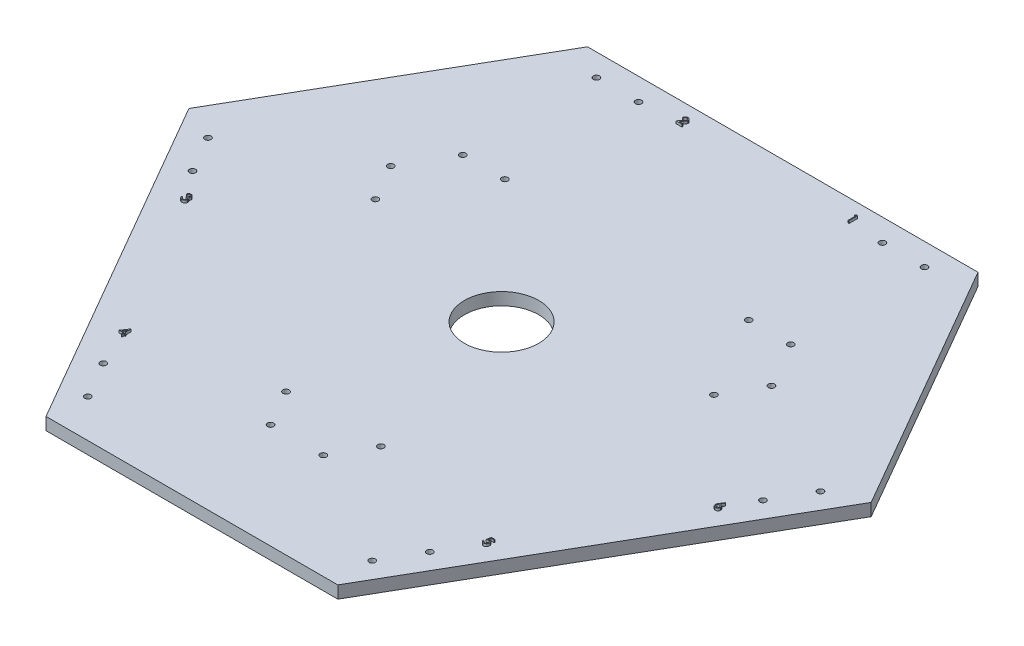
SolidWorks part; units mm, degrees
ref_plane "Front Plane" through (0, 0, 0) normal (0, 0, 1) x (1, 0, 0)
ref_plane "Top Plane" through (0, 0, 0) normal (0, 1, 0) x (1, 0, 0)
ref_plane "Right Plane" through (0, 0, 0) normal (1, 0, 0) x (0, 0, -1)
sketch "Sketch1" plane through (0, 0, 0) normal (0, 1, 0) x (1, 0, 0)
  line L0 (0, 0) -> (-57.7186, 110.8764) construction
  line L9 (0, 0) -> (0, 125) construction
  line L15 (0, 0) -> (57.7186, 110.8764) construction
  line L16 (-57.7186, 110.8764) -> (-12.7186, 110.8764) construction
  line L17 (-57.7186, 108.5064) -> (-57.7186, 110.8764) construction
  line L18 (-66.2186, 104.5064) -> (-49.2186, 104.5064) construction
  line L19 (-66.2186, 104.5064) -> (-66.2186, 50.5064) construction
  line L20 (-66.2186, 50.5064) -> (-49.2186, 50.5064) construction
  line L21 (-49.2186, 104.5064) -> (-49.2186, 50.5064) construction
  line L26 (-66.2186, 104.5064) -> (-49.2186, 50.5064) construction
  line L27 (-66.2186, 50.5064) -> (-49.2186, 104.5064) construction
  line L30 (-43.2186, 46.5064) -> (-72.2186, 46.5064) construction
  line L31 (-43.2186, 46.5064) -> (-43.2186, 108.5064) construction
  line L32 (-43.2186, 108.5064) -> (-72.2186, 108.5064) construction
  line L34 (-72.2186, 46.5064) -> (-72.2186, 108.5064) construction
  line L35 (-43.2186, 46.5064) -> (-72.2186, 108.5064) construction
  line L36 (-43.2186, 108.5064) -> (-72.2186, 46.5064) construction
  line L37 (43.2186, 108.5064) -> (72.2186, 46.5064) construction
  line L38 (43.2186, 46.5064) -> (72.2186, 108.5064) construction
  line L39 (72.2186, 46.5064) -> (72.2186, 108.5064) construction
  line L40 (43.2186, 108.5064) -> (72.2186, 108.5064) construction
  line L41 (43.2186, 46.5064) -> (43.2186, 108.5064) construction
  line L42 (43.2186, 46.5064) -> (72.2186, 46.5064) construction
  line L43 (66.2186, 50.5064) -> (49.2186, 104.5064) construction
  line L44 (66.2186, 104.5064) -> (49.2186, 50.5064) construction
  line L45 (49.2186, 104.5064) -> (49.2186, 50.5064) construction
  line L46 (66.2186, 50.5064) -> (49.2186, 50.5064) construction
  line L47 (66.2186, 104.5064) -> (66.2186, 50.5064) construction
  line L48 (66.2186, 104.5064) -> (49.2186, 104.5064) construction
  line L49 (57.7186, 108.5064) -> (57.7186, 110.8764) construction
  line L50 (57.7186, 110.8764) -> (12.7186, 110.8764) construction
  line L51 (0, 0) -> (124.881, -5.4524) construction
  line L52 (0, 0) -> (108.2532, -62.5) construction
  line L53 (0, 0) -> (67.1625, -105.4239) construction
  line L54 (124.881, -5.4524) -> (102.381, -44.4236) construction
  line L55 (122.8285, -4.2674) -> (124.881, -5.4524) construction
  line L56 (123.6144, 5.0938) -> (115.1144, -9.6286) construction
  line L57 (123.6144, 5.0938) -> (76.8491, 32.0938) construction
  line L58 (76.8491, 32.0938) -> (68.3491, 17.3714) construction
  line L59 (115.1144, -9.6286) -> (68.3491, 17.3714) construction
  line L60 (123.6144, 5.0938) -> (68.3491, 17.3714) construction
  line L61 (76.8491, 32.0938) -> (115.1144, -9.6286) construction
  line L62 (61.885, 14.1752) -> (76.385, 39.2899) construction
  line L63 (61.885, 14.1752) -> (115.5785, -16.8248) construction
  line L64 (115.5785, -16.8248) -> (130.0785, 8.2899) construction
  line L65 (76.385, 39.2899) -> (130.0785, 8.2899) construction
  line L66 (61.885, 14.1752) -> (130.0785, 8.2899) construction
  line L67 (115.5785, -16.8248) -> (76.385, 39.2899) construction
  line L68 (72.36, -91.6816) -> (4.1664, -85.7963) construction
  line L69 (18.6664, -60.6816) -> (57.86, -116.7963) construction
  line L70 (4.1664, -85.7963) -> (57.86, -116.7963) construction
  line L71 (72.36, -91.6816) -> (57.86, -116.7963) construction
  line L72 (18.6664, -60.6816) -> (72.36, -91.6816) construction
  line L73 (18.6664, -60.6816) -> (4.1664, -85.7963) construction
  line L74 (10.6305, -82.6001) -> (65.8959, -94.8777) construction
  line L75 (57.3959, -109.6001) -> (19.1305, -67.8777) construction
  line L76 (65.8959, -94.8777) -> (19.1305, -67.8777) construction
  line L77 (10.6305, -82.6001) -> (19.1305, -67.8777) construction
  line L78 (57.3959, -109.6001) -> (10.6305, -82.6001) construction
  line L79 (57.3959, -109.6001) -> (65.8959, -94.8777) construction
  line L80 (65.11, -104.2389) -> (67.1625, -105.4239) construction
  line L81 (67.1625, -105.4239) -> (89.6625, -66.4528) construction
  line L82 (0, 0) -> (-67.1625, -105.4239) construction
  line L83 (0, 0) -> (-108.2532, -62.5) construction
  line L84 (0, 0) -> (-124.881, -5.4524) construction
  line L85 (-67.1625, -105.4239) -> (-89.6625, -66.4528) construction
  line L86 (-65.11, -104.2389) -> (-67.1625, -105.4239) construction
  line L87 (-57.3959, -109.6001) -> (-65.8959, -94.8777) construction
  line L88 (-57.3959, -109.6001) -> (-10.6305, -82.6001) construction
  line L89 (-10.6305, -82.6001) -> (-19.1305, -67.8777) construction
  line L90 (-65.8959, -94.8777) -> (-19.1305, -67.8777) construction
  line L91 (-57.3959, -109.6001) -> (-19.1305, -67.8777) construction
  line L92 (-10.6305, -82.6001) -> (-65.8959, -94.8777) construction
  line L93 (-18.6664, -60.6816) -> (-4.1664, -85.7963) construction
  line L94 (-18.6664, -60.6816) -> (-72.36, -91.6816) construction
  line L95 (-72.36, -91.6816) -> (-57.86, -116.7963) construction
  line L96 (-4.1664, -85.7963) -> (-57.86, -116.7963) construction
  line L97 (-18.6664, -60.6816) -> (-57.86, -116.7963) construction
  line L98 (-72.36, -91.6816) -> (-4.1664, -85.7963) construction
  line L99 (-115.5785, -16.8248) -> (-76.385, 39.2899) construction
  line L100 (-61.885, 14.1752) -> (-130.0785, 8.2899) construction
  line L101 (-76.385, 39.2899) -> (-130.0785, 8.2899) construction
  line L102 (-115.5785, -16.8248) -> (-130.0785, 8.2899) construction
  line L103 (-61.885, 14.1752) -> (-115.5785, -16.8248) construction
  line L104 (-61.885, 14.1752) -> (-76.385, 39.2899) construction
  line L105 (-76.8491, 32.0938) -> (-115.1144, -9.6286) construction
  line L106 (-123.6144, 5.0938) -> (-68.3491, 17.3714) construction
  line L107 (-115.1144, -9.6286) -> (-68.3491, 17.3714) construction
  line L108 (-76.8491, 32.0938) -> (-68.3491, 17.3714) construction
  line L109 (-123.6144, 5.0938) -> (-76.8491, 32.0938) construction
  line L110 (-123.6144, 5.0938) -> (-115.1144, -9.6286) construction
  line L111 (-122.8285, -4.2674) -> (-124.881, -5.4524) construction
  line L112 (-124.881, -5.4524) -> (-102.381, -44.4236) construction
  line L119 (-78.8046, 113.5064) -> (78.8046, 113.5064)
  line L121 (-78.8046, 113.5064) -> (-137.7017, 11.4936)
  line L122 (-137.7017, 11.4936) -> (-58.8971, -125)
  line L123 (-58.8971, -125) -> (58.8971, -125)
  line L125 (137.7017, 11.4936) -> (58.8971, -125)
  line L126 (78.8046, 113.5064) -> (137.7017, 11.4936)
  circle A31 centre (0, 0) radius 125 construction
  circle A32 centre (-66.2186, 104.5064) radius 1.25
  circle A33 centre (-49.2186, 104.5064) radius 1.25
  circle A34 centre (-49.2186, 50.5064) radius 1.25
  circle A35 centre (-66.2186, 50.5064) radius 1.25
  circle A36 centre (66.2186, 50.5064) radius 1.25
  circle A37 centre (49.2186, 50.5064) radius 1.25
  circle A38 centre (49.2186, 104.5064) radius 1.25
  circle A39 centre (66.2186, 104.5064) radius 1.25
  circle A40 centre (123.6144, 5.0938) radius 1.25
  circle A41 centre (115.1144, -9.6286) radius 1.25
  circle A42 centre (68.3491, 17.3714) radius 1.25
  circle A43 centre (76.8491, 32.0938) radius 1.25
  circle A44 centre (10.6305, -82.6001) radius 1.25
  circle A45 centre (19.1305, -67.8777) radius 1.25
  circle A46 centre (65.8959, -94.8777) radius 1.25
  circle A47 centre (57.3959, -109.6001) radius 1.25
  circle A48 centre (-57.3959, -109.6001) radius 1.25
  circle A49 centre (-65.8959, -94.8777) radius 1.25
  circle A50 centre (-19.1305, -67.8777) radius 1.25
  circle A51 centre (-10.6305, -82.6001) radius 1.25
  circle A52 centre (-76.8491, 32.0938) radius 1.25
  circle A53 centre (-68.3491, 17.3714) radius 1.25
  circle A54 centre (-115.1144, -9.6286) radius 1.25
  circle A55 centre (-123.6144, 5.0938) radius 1.25
  circle A56 centre (0, 0) radius 15
  point P0 (-57.7186, 77.5064)
  point P3 (-57.7186, 77.5064)
  point P12 (-101.0203, 10.9895)
  point P14 (-40.993, -92.9809)
  point P16 (40.993, -92.9809)
  point P18 (101.0203, 10.9895)
  point P39 (57.7186, 77.5064)
  point P42 (95.9818, 11.2326)
  point P43 (95.9818, 11.2326)
  point P75 (38.2632, -88.7389)
  point P76 (-38.2632, -88.7389)
  point P77 (-38.2632, -88.7389)
  point P109 (-95.9818, 11.2326)
  point P110 (0, 0)
  point P116 (-108.2532, 62.5)
  point P118 (0, -125)
  point P120 (0, 113.5064)
  dimension "D1" = 55
  dimension "D6" = 54
  dimension "D11" = 5
  dimension "D3" = 250
  dimension "D9" = 2.5
  dimension "D13" = 30
  dimension "D2" = 3
  dimension "D4" = 45
  dimension "D5" = 17
  dimension "D8" = 62
  dimension "D7" = 29
  dimension "D10" = 2.37
  dimension "D12" = 5
extrude "Boss-Extrude1" add sketch "Sketch1" along normal blind 5
sketch "Sketch2" plane through (0, 5, 0) normal (0, 1, 0) x (1, 0, 0)
  line L0 (-115.1144, -9.6286) -> (-107.6144, -22.619) construction
  line L1 (-137.7017, 11.4936) -> (-58.8971, -125) construction
  line L2 (-65.8959, -94.8777) -> (-73.3959, -81.8873) construction
  line L3 (65.8959, -94.8777) -> (73.3959, -81.8873) construction
  line L4 (58.8971, -125) -> (137.7017, 11.4936) construction
  line L5 (115.1144, -9.6286) -> (107.6144, -22.619) construction
  line L6 (34.2186, 104.5064) -> (49.2186, 104.5064) construction
  line L7 (78.8046, 113.5064) -> (-78.8046, 113.5064) construction
  line L8 (-49.2186, 104.5064) -> (-34.2186, 104.5064) construction
  circle A0 centre (49.2186, 104.5064) radius 1.25 construction
  circle A1 centre (-49.2186, 104.5064) radius 1.25 construction
  circle A2 centre (-115.1144, -9.6286) radius 1.25 construction
  text T0 "1\r\n"
  text T1 "2\r\n"
  text T2 "3\r\n"
  text T3 "4\r\n"
  text T4 "5\r\n"
  text T5 "6\r\n"
  dimension "D1" = 15
  dimension "D3" = 15
  dimension "D5" = 15
  dimension "D6" = 15
  dimension "D7" = 15
  dimension "D8" = 15
extrude "Boss-Extrude2" add sketch "Sketch2" along normal blind 1
